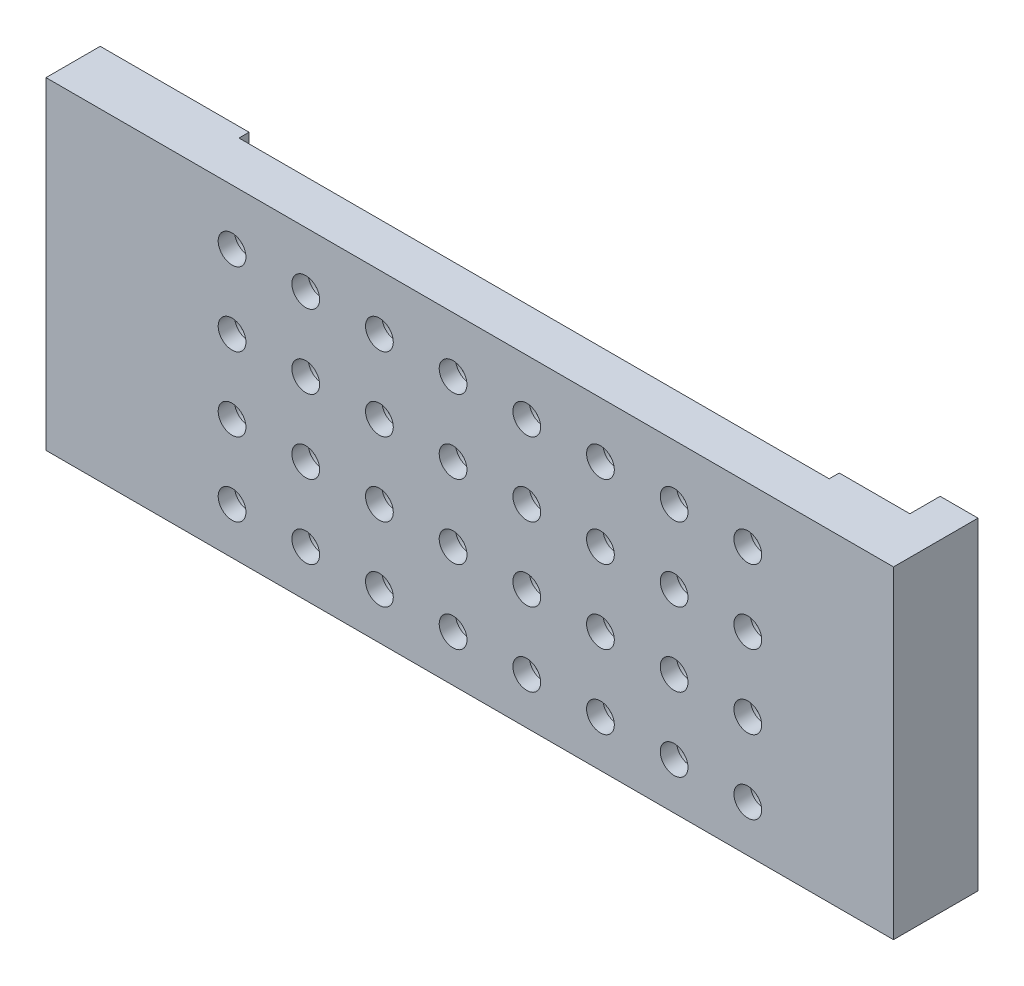
SolidWorks part; units mm, degrees
ref_plane "Front Plane" through (0, 0, 0) normal (0, 0, 1) x (1, 0, 0)
ref_plane "Top Plane" through (0, 0, 0) normal (0, 1, 0) x (1, 0, 0)
ref_plane "Right Plane" through (0, 0, 0) normal (1, 0, 0) x (0, 0, -1)
sketch "Sketch4" plane through (0, 0, 0) normal (-1, 0, 0) x (0, 0, 1)
  line L0 (8, 32) -> (16.75, 32)
  line L1 (8, -27.5) -> (8, -32)
  line L2 (8.75, -27.5) -> (8, -27.5)
  line L3 (8, -32) -> (16.75, -32)
  line L4 (8.75, 27.5) -> (8, 27.5)
  line L5 (8.75, 27.5) -> (8.75, -27.5)
  line L6 (8, 27.5) -> (8, 32)
  line L7 (-17.583, 0) -> (27.4771, 0) construction
  line L8 (16.75, -32) -> (16.75, 32)
  dimension "D1" = 8
  dimension "D2" = 4.5
  dimension "D3" = 0.75
  dimension "D4" = 64
extrude "Side Profile" add sketch "Sketch4" against normal blind 168
sketch "Sketch5" plane through (0, 0, 16.75) normal (0, 0, 1) x (1, 0, 0)
  line L1 (0, 32) -> (168, -32) construction
  line L2 (152, -32) -> (24, -32) construction
  line L3 (0, -32) -> (168, 32) construction
  line L4 (0, 32) -> (168, 32) construction
  line L5 (0, 32) -> (0, -32) construction
  line L6 (0, -32) -> (168, -32) construction
  line L7 (168, 32) -> (168, -32) construction
  line L8 (24, 32) -> (152, -32) construction
  line L9 (152, -32) -> (152, 32) construction
  line L14 (24, -32) -> (152, 32) construction
  line L15 (152, 32) -> (24, 32) construction
  line L16 (24, -32) -> (24, 32) construction
  line L17 (88, 0) -> (88, -52.578) construction
  circle A0 centre (36.8825, -22.8) radius 2.75
  circle A1 centre (51.4875, -22.8) radius 2.75
  circle A2 centre (66.0925, -22.8) radius 2.75
  circle A3 centre (80.6975, -22.8) radius 2.75
  circle A4 centre (95.3025, -22.8) radius 2.75
  circle A5 centre (109.9075, -22.8) radius 2.75
  circle A6 centre (124.5125, -22.8) radius 2.75
  circle A7 centre (139.1175, -22.8) radius 2.75
  circle A8 centre (51.4875, -8.195) radius 2.75
  circle A9 centre (66.0925, -8.195) radius 2.75
  circle A10 centre (80.6975, -8.195) radius 2.75
  circle A11 centre (95.3025, -8.195) radius 2.75
  circle A12 centre (109.9075, -8.195) radius 2.75
  circle A13 centre (124.5125, -8.195) radius 2.75
  circle A14 centre (139.1175, -8.195) radius 2.75
  circle A15 centre (51.4875, 6.41) radius 2.75
  circle A16 centre (66.0925, 6.41) radius 2.75
  circle A17 centre (80.6975, 6.41) radius 2.75
  circle A18 centre (95.3025, 6.41) radius 2.75
  circle A19 centre (109.9075, 6.41) radius 2.75
  circle A20 centre (124.5125, 6.41) radius 2.75
  circle A21 centre (139.1175, 6.41) radius 2.75
  circle A22 centre (51.4875, 21.015) radius 2.75
  circle A23 centre (66.0925, 21.015) radius 2.75
  circle A24 centre (80.6975, 21.015) radius 2.75
  circle A25 centre (95.3025, 21.015) radius 2.75
  circle A26 centre (109.9075, 21.015) radius 2.75
  circle A27 centre (124.5125, 21.015) radius 2.75
  circle A28 centre (139.1175, 21.015) radius 2.75
  circle A29 centre (36.8825, -8.195) radius 2.75
  circle A30 centre (36.8825, 6.41) radius 2.75
  circle A31 centre (36.8825, 21.015) radius 2.75
  point P3 (88, 0)
  point P76 (84, 0)
  dimension "D1" = 9.2
  dimension "D3" = 5.5
  dimension "D2" = 12.8825
  dimension "D6" = 14.605
  dimension "D7" = 14.605
  dimension "D8" = 12.8825
  dimension "D9" = 16
  dimension "D10" = 128
  dimension "D4" = 8
  dimension "D5" = 4
extrude "Tube Holes" cut sketch "Sketch5" against normal through all
sketch "Sketch7" plane through (0, 0, 8.75) normal (0, 0, -1) x (-1, 0, 0)
  line L0 (-168, -32) -> (0, -32) construction
  line L1 (-168, 32) -> (-160.5, 32)
  line L2 (-168, 32) -> (-168, -32)
  line L3 (-168, -32) -> (-160.5, -32)
  line L4 (-160.5, 32) -> (-160.5, -32)
  dimension "D1" = 7.5
extrude "Edge" add sketch "Sketch7" along normal blind 8.75
sketch "Sketch9" plane through (0, 0, 8) normal (0, 0, -1) x (-1, 0, 0)
  line L0 (-160.5, 32) -> (0, 32) construction
  line L1 (-161, 32) -> (-146.5, 32)
  line L2 (-161, 32) -> (-161, -32)
  line L3 (-161, -32) -> (-146.5, -32)
  line L4 (-146.5, 32) -> (-146.5, -32)
  line L5 (-160.5, -32) -> (0, -32) construction
  line L6 (-168, 32) -> (-168, -32) construction
  line L7 (0, 27.5) -> (0, -27.5) construction
  line L8 (0, 32) -> (-29.5, 32)
  line L9 (0, 32) -> (0, 24)
  line L10 (0, 24) -> (-29.5, 24)
  line L11 (-29.5, 32) -> (-29.5, 24)
  line L12 (0, -32) -> (-29.5, -32)
  line L13 (0, -32) -> (0, -24)
  line L14 (0, -24) -> (-29.5, -24)
  line L15 (-29.5, -32) -> (-29.5, -24)
  dimension "D1" = 14.5
  dimension "D2" = 7
  dimension "D3" = 29.5
  dimension "D4" = 8
extrude "Slider Helper" add sketch "Sketch9" along normal blind 2
sketch "Sketch6" plane through (0, 0, 8) normal (0, 0, -1) x (-1, 0, 0)
  line L6 (-146.1777, -29.75) -> (37.8223, -29.75) construction
  line L7 (-138.6652, 29.75) -> (45.3348, 29.75) construction
  line L8 (-88, -51.7782) -> (-88, 51.7782) construction
  line L9 (-160, -32) -> (0, -32) construction
  line L10 (-160, -32) -> (-160, 32) construction
  line L11 (-160, 32) -> (0, 32) construction
  circle A4 centre (-88, -29.75) radius 0.7937
  circle A5 centre (-128, 29.75) radius 0.7938
  circle A6 centre (-128, -29.75) radius 0.7938
  circle A7 centre (-46, -29.75) radius 0.7937
  circle A8 centre (-46, 29.75) radius 0.7937
  circle A9 centre (-88, 29.75) radius 0.7937
  point P22 (-88, 0)
  point P39 (-88, 0)
  dimension "D13" = 1.5875
  dimension "D14" = 1.5875
  dimension "D15" = 40
  dimension "D17" = 1.5875
  dimension "D18" = 1.5875
  dimension "D19" = 1.5875
  dimension "D20" = 1.5875
  dimension "D16" = 42
  dimension "D21" = 40
  dimension "D22" = 42
  dimension "D24" = 72
extrude "Magnet Holes (main)" cut sketch "Sketch6" against normal blind 4.5
sketch "Sketch8" plane through (0, 0, 0) normal (0, 0, -1) x (-1, 0, 0)
  line L0 (-164, 41.795) -> (-164, -49958.205) construction
  line L1 (-168, 32) -> (-168, -32) construction
  line L2 (-160.5, 32) -> (-168, 32) construction
  line L3 (-168, -32) -> (-160.5, -32) construction
  circle A0 centre (-164, 29.75) radius 0.7938
  circle A1 centre (-164, -29.75) radius 0.7938
  circle A2 centre (-164, 0) radius 0.7938
  dimension "D2" = 2.25
  dimension "D5" = 1.5875
  dimension "D6" = 1.5875
  dimension "D7" = 1.5875
  dimension "D1" = 4
  dimension "D3" = 2.25
  dimension "D4" = 32
extrude "Magnet Holes (divet)" cut sketch "Sketch8" against normal blind 4.5
sketch "Sketch10" plane through (0, 0, 6) normal (0, 0, -1) x (-1, 0, 0)
  line L0 (-146.5, 32) -> (-160.5, 32) construction
  line L1 (-4, 65.0152) -> (-4, -49934.9848) construction
  line L2 (-153, 66.2709) -> (-153, -49933.7291) construction
  line L3 (-138.1907, 29.75) -> (49861.8093, 29.75) construction
  line L4 (-193.7316, -29.75) -> (49806.2684, -29.75) construction
  line L5 (-160.5, -32) -> (-146.5, -32) construction
  line L6 (-168, 32) -> (-168, -32) construction
  line L7 (0, 27.5) -> (0, -27.5) construction
  circle A0 centre (-153, 29.75) radius 0.7938
  circle A1 centre (-153, -29.75) radius 0.7938
  circle A2 centre (-4, 29.75) radius 0.7937
  circle A3 centre (-4, -29.75) radius 0.7937
  dimension "D4" = 1.5875
  dimension "D6" = 1.5875
  dimension "D1" = 2.25
  dimension "D2" = 2.25
  dimension "D3" = 15
  dimension "D5" = 4
extrude "Magnet Holes (helper)" cut sketch "Sketch10" against normal blind 4.5
sketch "Sketch12" plane through (0, -32, 0) normal (0, -1, 0) x (1, 0, 0)
  line L0 (168, 0) -> (168, 16.75) construction
  line L3 (184.7187, 12.75) -> (-49815.2813, 12.75) construction
  line L4 (168, 16.75) -> (0, 16.75) construction
  circle A38 centre (164, 12.75) radius 2.5
  circle A39 centre (156, 12.75) radius 2.5 construction
  circle A40 centre (148, 12.75) radius 2.5
  circle A41 centre (140, 12.75) radius 2.5
  circle A42 centre (132, 12.75) radius 2.5 construction
  circle A43 centre (124, 12.75) radius 2.5 construction
  circle A44 centre (116, 12.75) radius 2.5
  circle A45 centre (108, 12.75) radius 2.5
  circle A46 centre (100, 12.75) radius 2.5
  circle A47 centre (92, 12.75) radius 2.5 construction
  circle A48 centre (84, 12.75) radius 2.5 construction
  circle A49 centre (76, 12.75) radius 2.5
  circle A50 centre (68, 12.75) radius 2.5
  circle A51 centre (60, 12.75) radius 2.5
  circle A52 centre (52, 12.75) radius 2.5
  circle A53 centre (44, 12.75) radius 2.5 construction
  circle A54 centre (36, 12.75) radius 2.5
  circle A55 centre (28, 12.75) radius 2.5
  circle A56 centre (20, 12.75) radius 2.5
  circle A57 centre (12, 12.75) radius 2.5
  circle A58 centre (4, 12.75) radius 2.5 construction
  dimension "D5" = 5
  dimension "D7" = 8
  dimension "D1" = 4
  dimension "D3" = 4
  dimension "D6" = 21
extrude "Lego Holes (bottom)" cut sketch "Sketch12" against normal blind 2
sketch "Sketch13" plane through (0, 0, 16.75) normal (0, 0, 1) x (1, 0, 0)
  line L1 (152, 32) -> (24, 32) construction
  line L2 (152, 32) -> (152, -32) construction
  line L3 (152, -32) -> (24, -32) construction
  line L4 (24, 32) -> (24, -32) construction
  line L5 (152, 32) -> (24, -32) construction
  line L6 (152, -32) -> (24, 32) construction
  circle A0 centre (36.8825, -22.8) radius 4
  circle A2 centre (51.4875, -22.8) radius 4
  circle A3 centre (66.0925, -22.8) radius 4
  circle A4 centre (80.6975, -22.8) radius 4
  circle A5 centre (95.3025, -22.8) radius 4
  circle A6 centre (109.9075, -22.8) radius 4
  circle A7 centre (124.5125, -22.8) radius 4
  circle A8 centre (139.1175, -22.8) radius 4
  circle A9 centre (51.4875, -8.195) radius 4
  circle A10 centre (66.0925, -8.195) radius 4
  circle A11 centre (80.6975, -8.195) radius 4
  circle A12 centre (95.3025, -8.195) radius 4
  circle A13 centre (109.9075, -8.195) radius 4
  circle A14 centre (124.5125, -8.195) radius 4
  circle A15 centre (139.1175, -8.195) radius 4
  circle A16 centre (51.4875, 6.41) radius 4
  circle A17 centre (66.0925, 6.41) radius 4
  circle A18 centre (80.6975, 6.41) radius 4
  circle A19 centre (95.3025, 6.41) radius 4
  circle A20 centre (109.9075, 6.41) radius 4
  circle A21 centre (124.5125, 6.41) radius 4
  circle A22 centre (139.1175, 6.41) radius 4
  circle A23 centre (51.4875, 21.015) radius 4
  circle A24 centre (66.0925, 21.015) radius 4
  circle A25 centre (80.6975, 21.015) radius 4
  circle A26 centre (95.3025, 21.015) radius 4
  circle A27 centre (109.9075, 21.015) radius 4
  circle A28 centre (124.5125, 21.015) radius 4
  circle A29 centre (139.1175, 21.015) radius 4
  circle A30 centre (36.8825, -8.195) radius 4
  circle A31 centre (36.8825, 6.41) radius 4
  circle A32 centre (36.8825, 21.015) radius 4
  point P0 (88, 0)
  dimension "D1" = 8
  dimension "D2" = 8
  dimension "D4" = 14.605
  dimension "D5" = 14.605
  dimension "D3" = 4
extrude "O-Ring Holes" cut sketch "Sketch13" against normal mid plane 1.5 from offset 4
